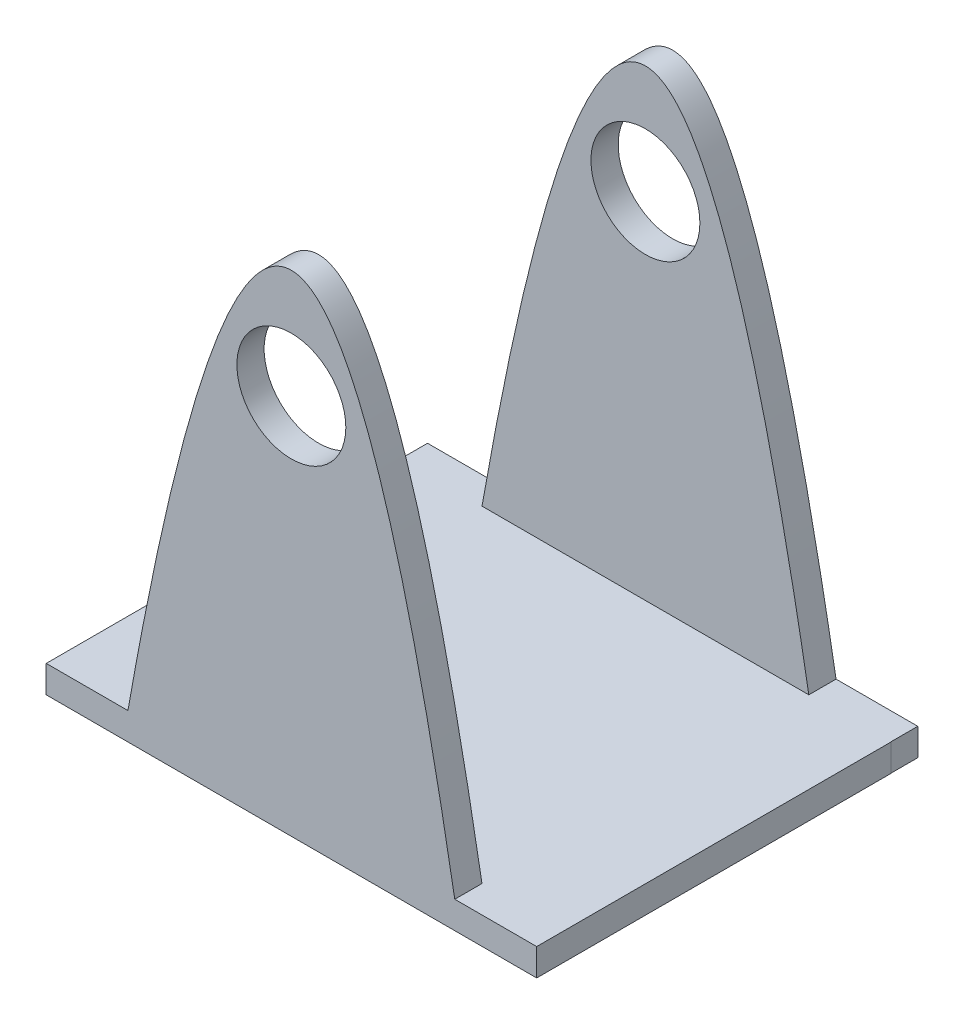
SolidWorks part; units mm, degrees
ref_plane "Front Plane" through (0, 0, 0) normal (0, 0, 1) x (1, 0, 0)
ref_plane "Top Plane" through (0, 0, 0) normal (0, 1, 0) x (1, 0, 0)
ref_plane "Right Plane" through (0, 0, 0) normal (1, 0, 0) x (0, 0, -1)
sketch "Sketch2" plane through (0, 0, 0) normal (0, 0, 1) x (1, 0, 0)
  line L0 (-76.2, 6.35) -> (-50.8, 6.35)
  line L1 (-76.2, -6.35) -> (76.2, -6.35)
  line L2 (-76.2, -6.35) -> (-76.2, 6.35)
  line L3 (-76.2, 6.35) -> (76.2, 6.35)
  line L4 (76.2, -6.35) -> (76.2, 6.35)
  line L5 (-76.2, -6.35) -> (76.2, 6.35) construction
  line L6 (-76.2, 6.35) -> (76.2, -6.35) construction
  line L7 (76.2, 6.35) -> (50.8, 6.35)
  line L8 (0, 6.35) -> (0, 222.25)
  line L9 (0, 6.35) -> (0, 19.05)
  line L10 (0, 19.05) -> (0, 171.45)
  line L11 (76.2, 6.35) -> (114.3, 6.35)
  line L12 (76.2, 6.35) -> (76.2, -6.35)
  line L13 (114.3, 6.35) -> (114.3, -6.35)
  line L14 (76.2, -6.35) -> (114.3, -6.35)
  line L15 (-76.2, 6.35) -> (-114.3, 6.35)
  line L16 (-76.2, 6.35) -> (-76.2, -6.35)
  line L17 (-114.3, 6.35) -> (-114.3, -6.35)
  line L18 (-76.2, -6.35) -> (-114.3, -6.35)
  circle A0 centre (0, 171.45) radius 25.4
  spline S0 degree 2 poles (-76.2, 6.35) (0, 438.15) (76.2, 6.35) knots 0 0 0 1 1 1
  point P0 (0, 0)
  dimension "D8" = 38.1
  dimension "D9" = 38.1
  dimension "D1" = 12.7
  dimension "D2" = 152.4
  dimension "D3" = 25.4
  dimension "D4" = 215.9
  dimension "D5" = 25.4
  dimension "D6" = 12.7
  dimension "D7" = 152.4
extrude "Boss-Extrude1" add sketch "Sketch2" along normal blind 12.7 contours S0 L0 L3 L8 A0 | S0 L8 A0 L3 | L18 L2 L15 L17 | L1 L4 L3 L0 L2 | L11 L13 L14 L12
sketch "Sketch4" plane through (0, 0, 12.7) normal (0, 0, 1) x (1, 0, 0)
  line L0 (-114.3, -6.35) -> (-114.3, 6.35)
  line L1 (-114.3, -6.35) -> (114.402, -6.35)
  line L2 (-114.3, 6.35) -> (114.402, 6.35)
  line L3 (114.402, -6.35) -> (114.402, 6.35)
extrude "Boss-Extrude2" add sketch "Sketch4" along normal blind 152.4
sketch "Sketch5" plane through (0, 0, 165.1) normal (0, 0, 1) x (1, 0, 0)
  line L0 (76.2, 6.35) -> (114.402, 6.35)
  line L1 (114.402, 6.35) -> (114.402, -6.35)
  line L2 (114.402, -6.35) -> (-114.3, -6.35)
  line L3 (-114.3, -6.35) -> (-114.3, 6.35)
  line L4 (-114.3, 6.35) -> (-76.2, 6.35)
  circle A0 centre (0, 171.45) radius 25.4
  parabola Q0 (-76.2, 6.35) -> (76.2, 6.35) focus (0, 215.5265) apex (0, 222.25) construction
  spline S0 degree 2 poles (-76.2, 6.35) (0, 438.15) (76.2, 6.35) knots 0 0 0 1 1 1
extrude "Boss-Extrude3" add sketch "Sketch5" along normal blind 12.7
